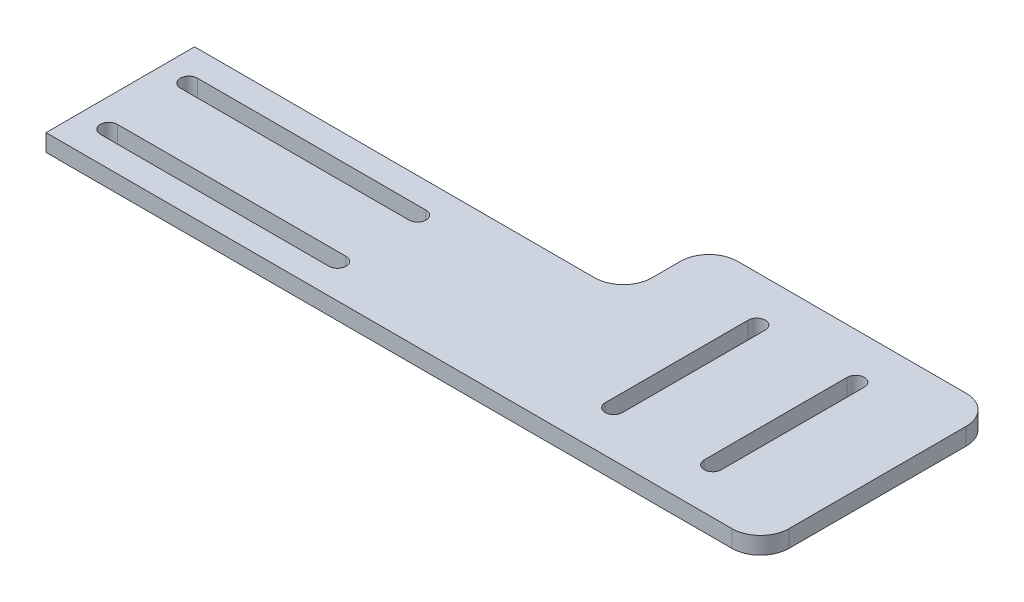
SolidWorks part; units mm, degrees
material "Titanium Ti-8Mn, Annealed"
ref_plane "Front Plane" through (0, 0, 0) normal (0, 0, 1) x (1, 0, 0)
ref_plane "Top Plane" through (0, 0, 0) normal (0, 1, 0) x (1, 0, 0)
ref_plane "Right Plane" through (0, 0, 0) normal (1, 0, 0) x (0, 0, -1)
sketch "Sketch1" plane through (0, 0, 0) normal (0, 1, 0) x (1, 0, 0)
  line L0 (0, 0) -> (75, 0)
  line L1 (75, 0) -> (75, 15)
  line L2 (75, 15) -> (125, 15)
  line L3 (125, 15) -> (125, -26)
  line L4 (125, -26) -> (0, -26)
  line L5 (0, -26) -> (0, 0)
  point P4 (0, -13)
  dimension "D1" = 26
  dimension "D2" = 15
  dimension "D3" = 50
  dimension "D4" = 125
extrude "Boss-Extrude1" add sketch "Sketch1" along normal blind 3
sketch "Sketch2" plane through (0, 3, 0) normal (0, 1, 0) x (1, 0, 0)
  line L0 (91.34, 7) -> (91.34, -18) construction
  line L1 (92.84, 7) -> (92.84, -18)
  line L2 (89.84, 7) -> (89.84, -18)
  line L3 (100, 11.1767) -> (100, -23.6501) construction
  line L4 (125, -26) -> (125, 15) construction
  line L5 (75, 15) -> (75, 0) construction
  line L6 (108.66, 7) -> (108.66, -18) construction
  line L7 (107.16, 7) -> (107.16, -18)
  line L8 (110.16, 7) -> (110.16, -18)
  line L12 (0, -26) -> (125, -26) construction
  arc A0 (92.84, 7) -> (89.84, 7) centre (91.34, 7) ccw
  arc A1 (89.84, -18) -> (92.84, -18) centre (91.34, -18) ccw
  arc A2 (107.16, 7) -> (110.16, 7) centre (108.66, 7) cw
  arc A3 (110.16, -18) -> (107.16, -18) centre (108.66, -18) cw
  point P2 (91.34, -5.5)
  point P17 (108.66, -5.5)
  dimension "D2" = 1.5
  dimension "D1" = 17.32
  dimension "D3" = 25
  dimension "D4" = 20.5
extrude "Cut-Extrude1" cut sketch "Sketch2" against normal blind 3
fillet "Fillet1" radius 5 4 edges at (75, 1.5, 0) (75, 1.5, -15) (125, 1.5, 26) (125, 1.5, -15)
sketch "Sketch4" plane through (0, 3, 0) normal (0, 1, 0) x (1, 0, 0)
  line L0 (45, -20) -> (5, -20) construction
  line L1 (45, -21.5) -> (5, -21.5)
  line L2 (45, -18.5) -> (5, -18.5)
  line L3 (41.1128, -13) -> (7.2469, -13) construction
  line L4 (45, -6) -> (5, -6) construction
  line L5 (45, -4.5) -> (5, -4.5)
  line L6 (45, -7.5) -> (5, -7.5)
  line L7 (0, -26) -> (120, -26) construction
  line L8 (70, 0) -> (0, 0) construction
  line L9 (0, 0) -> (0, -26) construction
  arc A0 (45, -21.5) -> (45, -18.5) centre (45, -20) ccw
  arc A1 (5, -18.5) -> (5, -21.5) centre (5, -20) ccw
  arc A2 (45, -4.5) -> (45, -7.5) centre (45, -6) cw
  arc A3 (5, -7.5) -> (5, -4.5) centre (5, -6) cw
  point P2 (25, -20)
  point P11 (25, -6)
  dimension "D4" = 1.5
  dimension "D1" = 25
  dimension "D2" = 14
  dimension "D3" = 40
extrude "Cut-Extrude2" cut sketch "Sketch4" against normal through all
